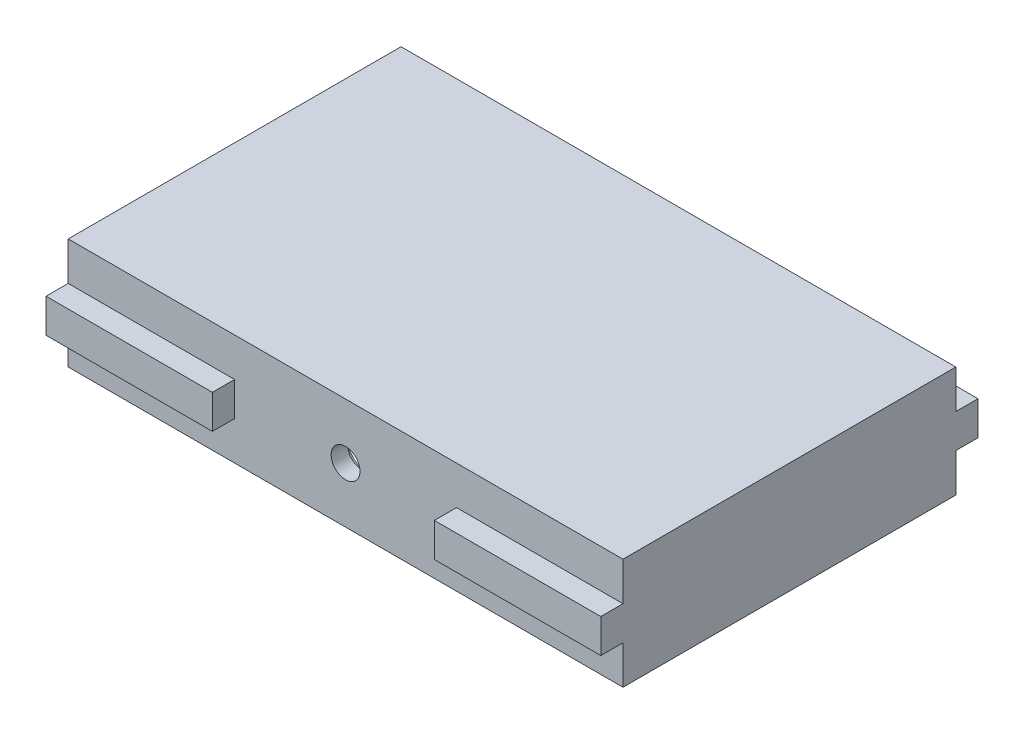
SolidWorks part; units mm, degrees
ref_plane "前视基准面" through (0, 0, 0) normal (0, 0, 1) x (1, 0, 0)
ref_plane "上视基准面" through (0, 0, 0) normal (0, 1, 0) x (1, 0, 0)
ref_plane "右视基准面" through (0, 0, 0) normal (1, 0, 0) x (0, 0, -1)
other "Configuration Table"
sketch "草图1" plane through (0, 0, 0) normal (0, 1, 0) x (1, 0, 0)
  line L1 (-20.4498, 16.4446) -> (79.5502, 16.4446)
  line L2 (-20.4498, 16.4446) -> (-20.4498, -43.5554)
  line L3 (-20.4498, -43.5554) -> (79.5502, -43.5554)
  line L4 (79.5502, 16.4446) -> (79.5502, -43.5554)
extrude "凸台-拉伸1" add sketch "草图1" along normal blind 20
sketch "草图2" plane through (0, 0, 0) normal (0, -1, 0) x (1, 0, 0)
  line L1 (-20.4498, 43.5554) -> (-15.4498, 43.5554)
  line L2 (-20.4498, 43.5554) -> (-20.4498, 38.5554)
  line L3 (-20.4498, 38.5554) -> (-15.4498, 38.5554)
  line L4 (-15.4498, 43.5554) -> (-15.4498, 38.5554)
  line L5 (79.5502, -16.4446) -> (74.5502, -16.4446)
  line L6 (79.5502, -16.4446) -> (79.5502, -11.4446)
  line L7 (79.5502, -11.4446) -> (74.5502, -11.4446)
  line L8 (74.5502, -16.4446) -> (74.5502, -11.4446)
  line L9 (-15.4498, 38.5554) -> (74.5502, 38.5554)
  line L10 (-15.4498, 38.5554) -> (-15.4498, -11.4446)
  line L11 (-15.4498, -11.4446) -> (74.5502, -11.4446)
  line L12 (74.5502, 38.5554) -> (74.5502, -11.4446)
extrude "切除-拉伸1" cut sketch "草图2" against normal blind 15 contours L12 L9 L10 L11
sketch "草图8" plane through (0, 0, 43.5554) normal (0, 0, 1) x (1, 0, 0)
  line L0 (29.5502, 20) -> (29.5502, 0)
  line L1 (-20.4498, 20) -> (79.5502, 20) construction
  line L2 (-20.4498, 0) -> (79.5502, 0) construction
  circle A0 centre (29.5502, 10) radius 2.6
extrude "切除-拉伸6" cut sketch "草图8" against normal blind 200 contours L0 A0 | L0 A0
sketch "草图9" plane through (0, 0, -11.4446) normal (0, 0, 1) x (1, 0, 0)
  circle A0 centre (29.5502, 10) radius 5
extrude "切除-拉伸7" cut sketch "草图9" against normal blind 2
sketch "草图10" plane through (0, 0, 38.5554) normal (0, 0, -1) x (-1, 0, 0)
  circle A0 centre (-29.5502, 10) radius 5
extrude "切除-拉伸8" cut sketch "草图10" against normal blind 2
sketch "草图11" plane through (0, 0, -16.4446) normal (0, 0, -1) x (-1, 0, 0)
  line L0 (-29.5502, 10) -> (-79.5502, 10)
  line L1 (-79.5502, 20) -> (-79.5502, 0) construction
  line L2 (-29.5502, 10) -> (20.4498, 10)
  line L3 (20.4498, 20) -> (20.4498, 0) construction
  line L4 (20.4498, 10) -> (20.4498, 6.95)
  line L5 (-79.5502, 10) -> (-79.5502, 13.05)
  line L7 (-79.5502, 13.05) -> (-49.5502, 13.05)
  line L8 (-79.5502, 13.05) -> (-79.5502, 6.95)
  line L9 (-79.5502, 6.95) -> (-49.5502, 6.95)
  line L10 (-49.5502, 13.05) -> (-49.5502, 6.95)
  line L11 (20.4498, 6.95) -> (-9.5502, 6.95)
  line L12 (20.4498, 6.95) -> (20.4498, 13.05)
  line L13 (20.4498, 13.05) -> (-9.5502, 13.05)
  line L14 (-9.5502, 6.95) -> (-9.5502, 13.05)
  line M13 (20.4498, 0) -> (20.4498, 20)
  line M15 (-79.5502, 20) -> (-79.5502, 0)
extrude "凸台-拉伸2" add sketch "草图11" along normal blind 4 contours L14 L11 L2 M13 | L14 L2 L13 M13 | L10 L0 L9 M15 | L10 L7 L0 M15
sketch "草图12" plane through (0, 0, 43.5554) normal (0, 0, 1) x (1, 0, 0)
  line L0 (29.5502, 10) -> (79.5502, 10)
  line L1 (79.5502, 20) -> (79.5502, 0) construction
  line L2 (29.5502, 10) -> (-20.4498, 10)
  line L3 (-20.4498, 20) -> (-20.4498, 0) construction
  line L4 (-20.4498, 10) -> (-20.4498, 13.05)
  line L5 (79.5502, 10) -> (79.5502, 6.95)
  line L7 (-20.4498, 13.05) -> (9.5502, 13.05)
  line L8 (-20.4498, 13.05) -> (-20.4498, 6.95)
  line L9 (-20.4498, 6.95) -> (9.5502, 6.95)
  line L10 (9.5502, 13.05) -> (9.5502, 6.95)
  line L11 (79.5502, 6.95) -> (49.5502, 6.95)
  line L12 (79.5502, 6.95) -> (79.5502, 13.05)
  line L13 (79.5502, 13.05) -> (49.5502, 13.05)
  line L14 (49.5502, 6.95) -> (49.5502, 13.05)
  line M6 (79.5502, 0) -> (79.5502, 20)
  line M8 (-20.4498, 20) -> (-20.4498, 0)
extrude "凸台-拉伸3" add sketch "草图12" along normal blind 4 contours L10 L7 L2 M8 | L10 L2 L9 M8 | L14 L0 L13 M6 | L14 L11 L0 M6
